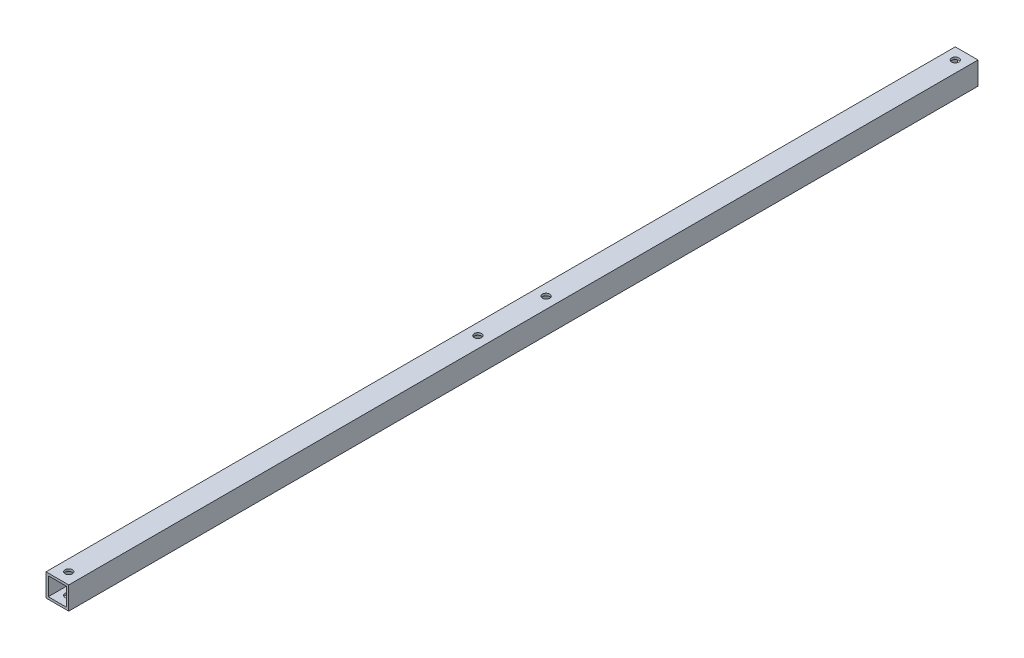
SolidWorks part; units mm, degrees
ref_plane "正面" through (0, 0, 0) normal (0, 0, 1) x (1, 0, 0)
ref_plane "平面" through (0, 0, 0) normal (0, 1, 0) x (1, 0, 0)
ref_plane "右側面" through (0, 0, 0) normal (1, 0, 0) x (0, 0, -1)
sketch "ｽｹｯﾁ1" plane through (0, 0, 0) normal (0, 0, 1) x (1, 0, 0)
  line L0 (-4, 4) -> (-4, -4)
  line L1 (-5, 5) -> (5, 5)
  line L2 (-5, 5) -> (-5, -5)
  line L3 (-5, -5) -> (5, -5)
  line L4 (5, 5) -> (5, -5)
  line L5 (-5, 5) -> (5, -5) construction
  line L6 (-5, -5) -> (5, 5) construction
  line L7 (-4, -4) -> (4, -4)
  line L8 (4, 4) -> (4, -4)
  line L9 (-4, 4) -> (4, 4)
  point P0 (0, 0)
  dimension "D1" = 10
  dimension "D2" = 10
  dimension "D3" = 1
extrude "ﾎﾞｽ - 押し出し1" add sketch "ｽｹｯﾁ1" along normal blind 399.7114
sketch "ｽｹｯﾁ2" plane through (0, 5, 0) normal (0, 1, 0) x (1, 0, 0)
  line L0 (5, -399.7114) -> (-5, -399.7114) construction
  line L1 (5, 0) -> (-5, 0) construction
  line L2 (-5, -399.7114) -> (-5, 0) construction
  circle A0 centre (0, -5) radius 1.6
  circle A1 centre (0, -394.7114) radius 1.6
  circle A2 centre (0, -184.8557) radius 1.6
  circle A3 centre (0, -214.8557) radius 1.6
  point P14 (-5, -199.8557)
  dimension "D1" = 5
  dimension "D2" = 3.2
  dimension "D3" = 5
  dimension "D4" = 3.2
  dimension "D5" = 15
  dimension "D6" = 15
  dimension "D7" = 3.2
  dimension "D8" = 3.2
extrude "ｶｯﾄ - 押し出し1" cut sketch "ｽｹｯﾁ2" against normal blind 408.3717
